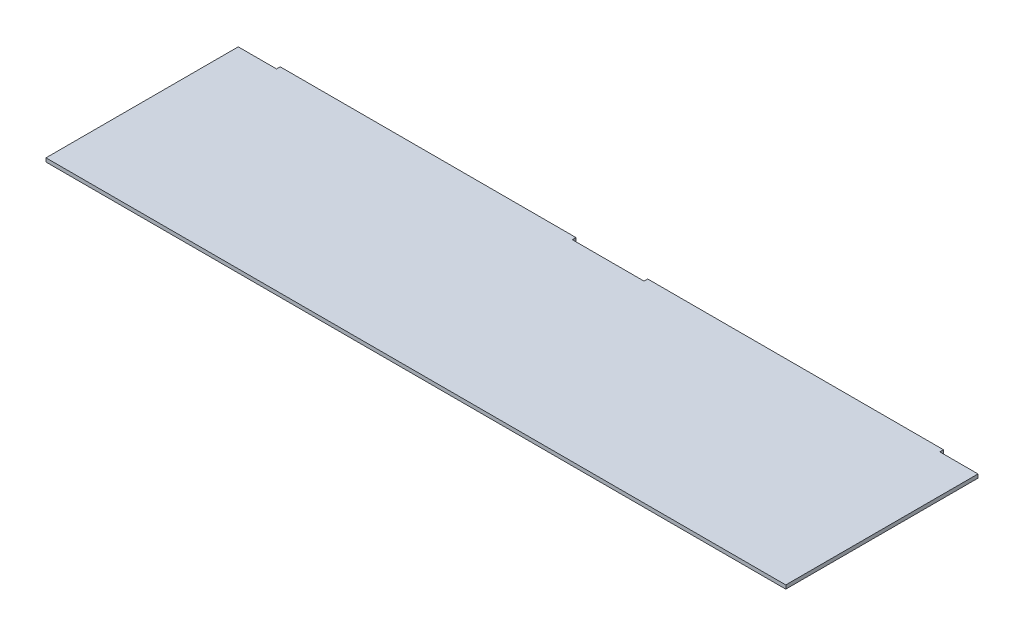
SolidWorks part; units mm, degrees
material "6061-T6 (SS)"
ref_plane "X-Y Datum" through (0, 0, 0) normal (0, 0, 1) x (1, 0, 0)
ref_plane "X-Z Datum" through (0, 0, 0) normal (0, 1, 0) x (1, 0, 0)
ref_plane "Y-Z Datum" through (0, 0, 0) normal (1, 0, 0) x (0, 0, -1)
sketch "Sketch1" plane through (0, 0, 0) normal (0, 1, 0) x (1, 0, 0)
  line L1 (-317.6778, 82.55) -> (317.6778, 82.55)
  line L2 (-317.6778, 82.55) -> (-317.6778, -82.55)
  line L3 (-317.6778, -82.55) -> (317.6778, -82.55)
  line L4 (317.6778, 82.55) -> (317.6778, -82.55)
  line L5 (-317.6778, 82.55) -> (317.6778, -82.55) construction
  line L6 (-317.6778, -82.55) -> (317.6778, 82.55) construction
  point P0 (0, 0)
  dimension "D1" = 635.3556
  dimension "D2" = 165.1
extrude "Boss-Extrude1" add sketch "Sketch1" along normal mid plane 3.175
sketch "Sketch2" plane through (0, 0, -82.55) normal (0, 0, -1) x (-1, 0, 0)
  line L20 (-317.6778, -1.5875) -> (317.6778, -1.5875) construction
  line L21 (-284.8229, -1.5875) -> (-30.8229, -1.5875)
  line L22 (30.8229, -1.5875) -> (284.8229, -1.5875)
  line L40 (30.8229, -1.5875) -> (30.8229, 1.5875)
  line L41 (30.8229, 1.5875) -> (284.8229, 1.5875)
  line L42 (284.8229, 1.5875) -> (284.8229, -1.5875)
  line L56 (-284.8229, -1.5875) -> (-284.8229, 1.5875)
  line L57 (-284.8229, 1.5875) -> (-30.8229, 1.5875)
  line L58 (-30.8229, 1.5875) -> (-30.8229, -1.5875)
extrude "Boss-Extrude2" add sketch "Sketch2" along normal blind 3.175
